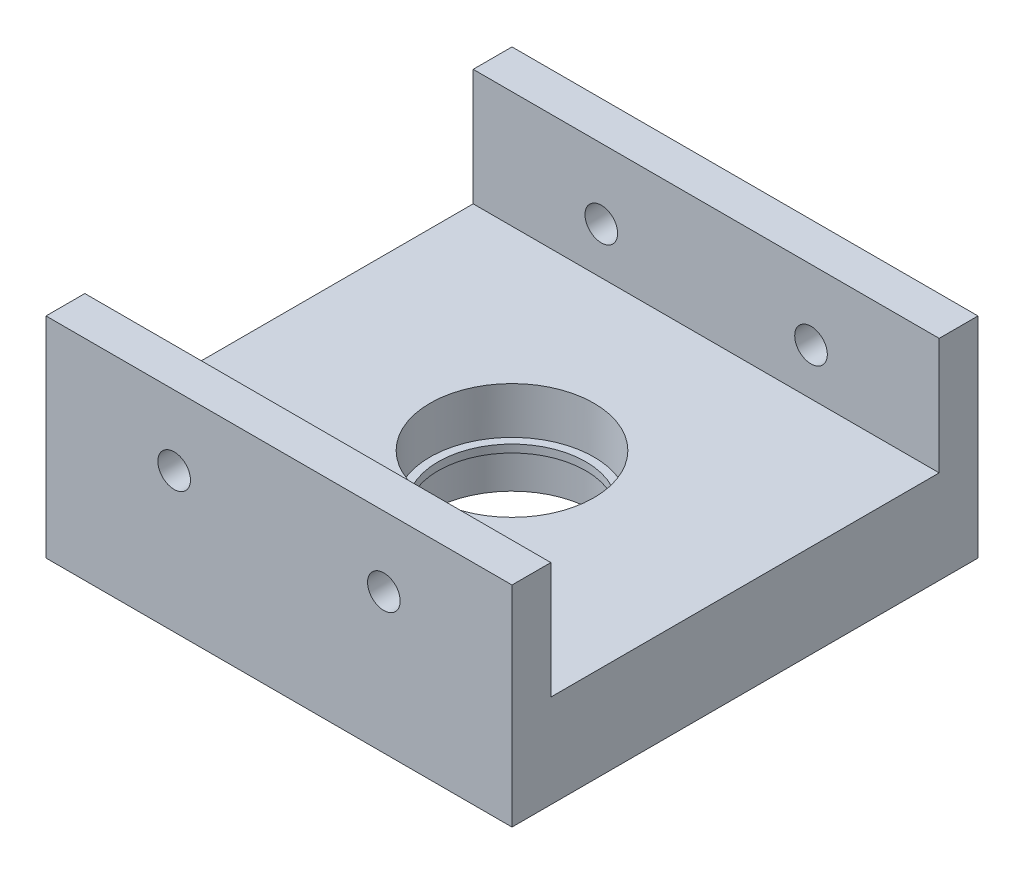
SolidWorks part; units mm, degrees
material "6061-T6 (SS)"
ref_plane "前视基准面" through (0, 0, 0) normal (0, 0, 1) x (1, 0, 0)
ref_plane "上视基准面" through (0, 0, 0) normal (0, 1, 0) x (1, 0, 0)
ref_plane "右视基准面" through (0, 0, 0) normal (1, 0, 0) x (0, 0, -1)
sketch "草图1" plane through (0, 0, 0) normal (0, 1, 0) x (1, 0, 0)
  line L1 (-30, -30) -> (30, -30)
  line L2 (-30, -30) -> (-30, 30)
  line L3 (-30, 30) -> (30, 30)
  line L4 (30, -30) -> (30, 30)
  line L5 (0, 30) -> (0, -30) construction
  line L6 (-30, 0) -> (30, 0) construction
  circle A0 centre (0, 0) radius 9.5
  point P0 (0, 0)
  dimension "D3" = 19
  dimension "D1" = 60
  dimension "D2" = 60
extrude "凸台-拉伸1" add sketch "草图1" along normal blind 12
ref_plane "基准面1" through (0, 6, 0) normal (0, -1, 0) x (-1, 0, 0)
sketch "草图3" plane through (0, 0, 0) normal (0, -1, 0) x (1, 0, 0)
  circle A0 centre (0, 0) radius 10.55
  dimension "D1" = 21.1
extrude "切除-拉伸1" cut sketch "草图3" against normal blind 5
mirror "镜向1" about plane through (0, 6, 0) normal (0, -1, 0) of "切除-拉伸1"
sketch "草图5" plane through (0, 0, -30) normal (0, 0, -1) x (-1, 0, 0)
  line L0 (-30, 6) -> (30, 6) construction
  line L1 (-30, 12) -> (-30, 0) construction
  line L2 (30, 12) -> (30, 0) construction
  line L3 (0, 12) -> (0, 0) construction
  line L4 (-30, 12) -> (30, 12) construction
  circle A0 centre (-40, 6) radius 1.5
  circle A1 centre (40, 6) radius 1.5
  point P11 (-40, 6)
  point P12 (40, 6)
  dimension "D1" = 40
ref_plane "孔对称面" through (0, 0, 0) normal (0, 0, -1) x (-1, 0, 0)
sketch "草图6" plane through (0, 12, 0) normal (0, 1, 0) x (1, 0, 0)
  line L0 (30, 30) -> (-30, 30)
  line L1 (30, 30) -> (30, 25)
  line L2 (-30, 30) -> (-30, 25)
  line L3 (30, 25) -> (-30, 25)
  line L4 (30, 0) -> (-30, 0) construction
  line L5 (30, -30) -> (30, 30) construction
  line L6 (-30, 30) -> (-30, -30) construction
  line L7 (-30, -30) -> (-30, -25)
  line L8 (30, -30) -> (-30, -30)
  line L9 (30, -30) -> (30, -25)
  line L10 (30, -25) -> (-30, -25)
  dimension "D1" = 5
extrude "凸台-拉伸2" add sketch "草图6" along normal blind 15
sketch "草图7" plane through (0, 0, 30) normal (0, 0, 1) x (1, 0, 0)
  line L0 (-30, 0) -> (30, 0) construction
  line L1 (0, 27) -> (0, 0) construction
  line L2 (-30, 27) -> (30, 27) construction
  circle A0 centre (-13.5, 18) radius 2.1
  circle A1 centre (13.5, 18) radius 2.1
  dimension "D1" = 18
  dimension "D3" = 4.2
  dimension "D2" = 27
extrude "切除-拉伸2" cut sketch "草图7" against normal through all
sketch "草图8" plane through (0, 7, 0) normal (0, 1, 0) x (1, 0, 0)
  circle A0 centre (0, 0) radius 10.55
  circle A1 centre (0, 0) radius 10.55 construction
extrude "切除-拉伸3" cut sketch "草图8" against normal blind 1
